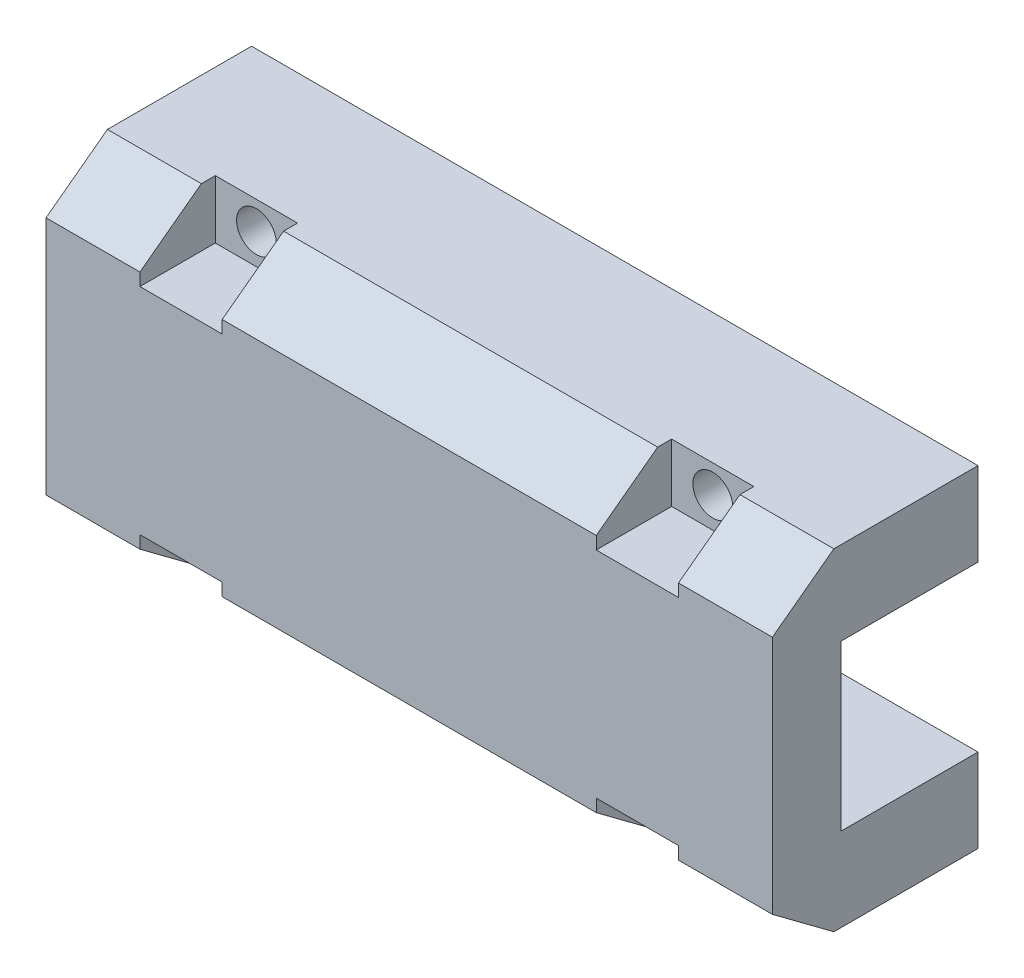
SolidWorks part; units mm, degrees
ref_plane "Alzado" through (0, 0, 0) normal (0, 0, 1) x (1, 0, 0)
ref_plane "Planta" through (0, 0, 0) normal (0, 1, 0) x (1, 0, 0)
ref_plane "Vista lateral" through (0, 0, 0) normal (1, 0, 0) x (0, 0, -1)
sketch "Croquis1" plane through (0, 0, 0) normal (0, 0, 1) x (1, 0, 0)
  line L1 (-27.6185, -5.8743) -> (25.3815, -5.8743)
  line L2 (-27.6185, -5.8743) -> (-27.6185, -11.9743)
  line L3 (-27.6185, -11.9743) -> (25.3815, -11.9743)
  line L4 (25.3815, -5.8743) -> (25.3815, -11.9743)
  line L5 (-27.6185, -23.9743) -> (25.3815, -23.9743)
  line L6 (-27.6185, -23.9743) -> (-27.6185, -30.0743)
  line L7 (-27.6185, -30.0743) -> (25.3815, -30.0743)
  line L8 (25.3815, -23.9743) -> (25.3815, -30.0743)
  dimension "D1" = 6.1
  dimension "D2" = 53
  dimension "D3" = 6.1
  dimension "D4" = 53
extrude "Saliente-Extruir1" add sketch "Croquis1" along normal blind 10
sketch "Croquis2" plane through (0, 0, 10) normal (0, 0, 1) x (1, 0, 0)
  line L1 (-27.6185, -5.8743) -> (25.3815, -5.8743)
  line L2 (-27.6185, -5.8743) -> (-27.6185, -30.0743)
  line L3 (-27.6185, -30.0743) -> (25.3815, -30.0743)
  line L4 (25.3815, -5.8743) -> (25.3815, -30.0743)
  dimension "D1" = 24.2
  dimension "D2" = 53
extrude "Saliente-Extruir2" add sketch "Croquis2" along normal blind 5
sketch "Croquis3" plane through (-27.6185, 0, 0) normal (-1, 0, 0) x (0, 0, 1)
  line L0 (10.5174, -5.8743) -> (15, -9.2166)
  line L1 (15, -5.8743) -> (0, -5.8743) construction
  line L2 (15, -5.8743) -> (15, -30.0743) construction
  line L3 (15, -9.2166) -> (15, -5.8743)
  line L4 (15, -5.8743) -> (10.5174, -5.8743)
  line L5 (15, -17.9743) -> (10.5174, -17.9743) construction
  line L6 (15, -26.7321) -> (15, -30.0743)
  line L7 (15, -30.0743) -> (10.5174, -30.0743)
  line L8 (10.5174, -30.0743) -> (15, -26.7321)
extrude "Cortar-Extruir1" cut sketch "Croquis3" against normal blind 100
sketch "Croquis4" plane through (0, -30.0743, 0) normal (0, -1, 0) x (1, 0, 0)
  line L0 (-27.6185, 0) -> (25.3815, 0) construction
  line L1 (-10.8685, 0) -> (8.6315, 0)
  line L2 (-10.8685, 0) -> (-10.8685, 3.2)
  line L3 (-10.8685, 3.2) -> (8.6315, 3.2)
  line L4 (8.6315, 0) -> (8.6315, 3.2)
  line L5 (-27.6185, 10.5174) -> (-27.6185, 0) construction
  dimension "D1" = 3.2
  dimension "D2" = 19.5
  dimension "D3" = 16.75
extrude "Cortar-Extruir2" cut sketch "Croquis4" against normal blind 10
sketch "Croquis5" plane through (0, 0, 15) normal (0, 0, 1) x (1, 0, 0)
  line L1 (-20.7656, -25.8108) -> (-14.7656, -25.8108)
  line L2 (-20.7656, -25.8108) -> (-20.7656, -30.0743)
  line L3 (-20.7656, -30.0743) -> (-14.7656, -30.0743)
  line L4 (-14.7656, -25.8108) -> (-14.7656, -30.0743)
  line L7 (25.3815, -30.0743) -> (-27.6185, -30.0743) construction
  line L9 (-20.7656, -5.8743) -> (-14.7656, -5.8743)
  line L10 (-20.7656, -5.8743) -> (-20.7656, -10.1345)
  line L11 (-20.7656, -10.1345) -> (-14.7656, -10.1345)
  line L12 (-14.7656, -5.8743) -> (-14.7656, -10.1345)
  line L14 (25.3815, -5.8743) -> (-27.6185, -5.8743) construction
  line L16 (-1.1185, -5.8743) -> (-1.1185, -30.0743) construction
  line L17 (12.5287, -25.8108) -> (12.5287, -30.0743)
  line L18 (18.5287, -25.8108) -> (12.5287, -25.8108)
  line L19 (18.5287, -30.0743) -> (12.5287, -30.0743)
  line L20 (18.5287, -25.8108) -> (18.5287, -30.0743)
  line L21 (18.5287, -5.8743) -> (12.5287, -5.8743)
  line L22 (12.5287, -5.8743) -> (12.5287, -10.1345)
  line L23 (18.5287, -10.1345) -> (12.5287, -10.1345)
  line L24 (18.5287, -5.8743) -> (18.5287, -10.1345)
  dimension "D1" = 4.2636
  dimension "D2" = 6
  dimension "D3" = 4.2602
  dimension "D4" = 6
extrude "Cortar-Extruir3" cut sketch "Croquis5" against normal blind 5.5
sketch "Croquis6" plane through (0, 0, 9.5) normal (0, 0, 1) x (1, 0, 0)
  line L0 (-27.6185, -17.9743) -> (25.3815, -17.9743) construction
  line L1 (-27.6185, -9.2166) -> (-27.6185, -26.7321) construction
  line L2 (25.3815, -26.7321) -> (25.3815, -9.2166) construction
  circle A0 centre (-17.7656, -7.9155) radius 1.45
  circle A1 centre (15.5287, -7.9155) radius 1.45
  circle A2 centre (15.5287, -28.0332) radius 1.45
  circle A3 centre (-17.7656, -28.0332) radius 1.45
  dimension "D1" = 2.9
  dimension "D2" = 2.9
extrude "Cortar-Extruir4" cut sketch "Croquis6" against normal blind 20
